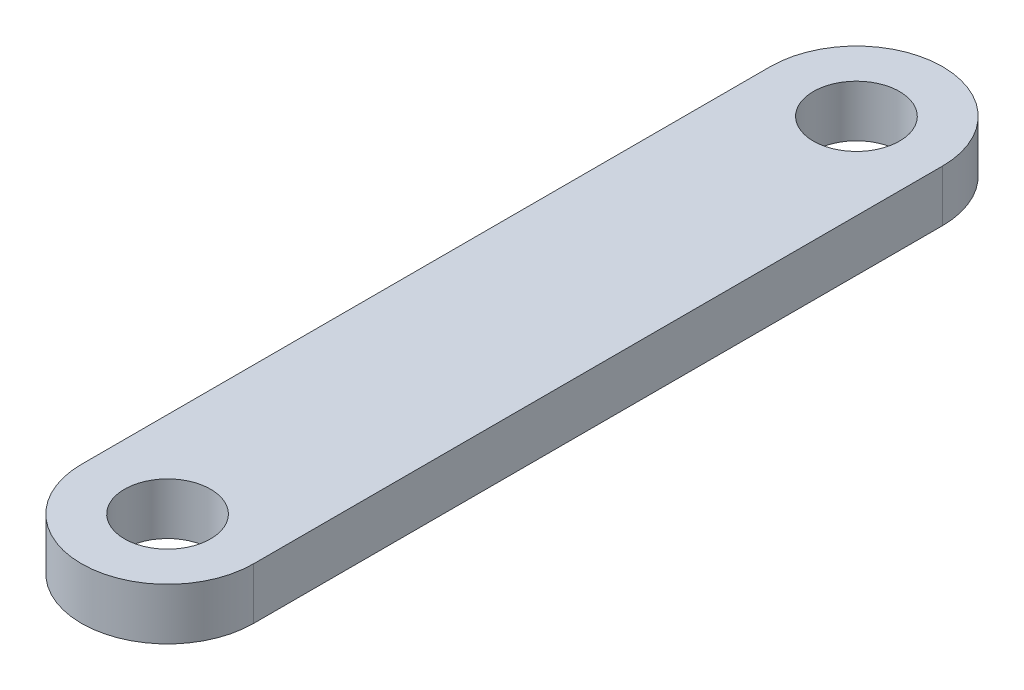
SolidWorks part; units mm, degrees
ref_plane "Front Plane" through (0, 0, 0) normal (0, 0, 1) x (1, 0, 0)
ref_plane "Top Plane" through (0, 0, 0) normal (0, 1, 0) x (1, 0, 0)
ref_plane "Right Plane" through (0, 0, 0) normal (1, 0, 0) x (0, 0, -1)
sketch "Sketch2" plane through (0, 0, 0) normal (0, 1, 0) x (1, 0, 0)
  line L0 (0, 0) -> (0, 160) construction
  line L1 (-20, 0) -> (-20, 160)
  line L2 (20, 0) -> (20, 160)
  arc A0 (-20, 0) -> (20, 0) centre (0, 0) ccw
  arc A1 (20, 160) -> (-20, 160) centre (0, 160) ccw
  point P3 (0, 80)
extrude "Boss-Extrude1" add sketch "Sketch2" along normal blind 12
sketch "Sketch3" plane through (0, 12, 0) normal (0, 1, 0) x (1, 0, 0)
  circle A0 centre (0, 0) radius 10
  dimension "D1" = 20
sketch "Sketch4" plane through (0, 12, 0) normal (0, 1, 0) x (1, 0, 0)
  circle A0 centre (0, 160) radius 10
  dimension "D1" = 20
extrude "Cut-Extrude1" cut sketch "Sketch4" against normal blind 30
extrude "Cut-Extrude2" cut sketch "Sketch3" against normal blind 30 contours A0
